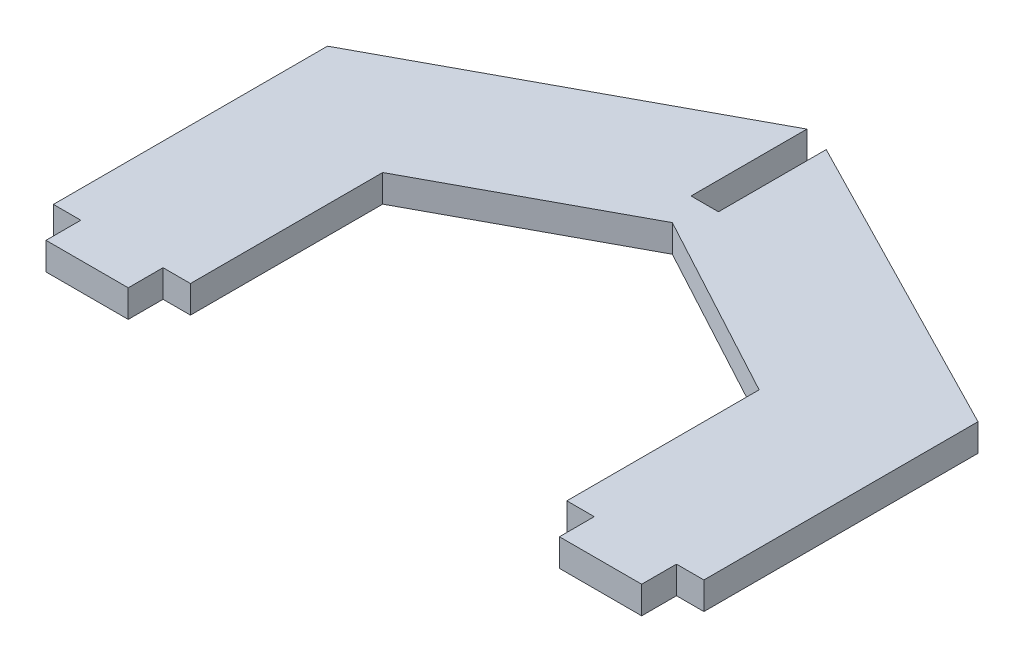
SolidWorks part; units mm, degrees
ref_plane "Front Plane" through (0, 0, 0) normal (0, 0, 1) x (1, 0, 0)
ref_plane "Top Plane" through (0, 0, 0) normal (0, 1, 0) x (1, 0, 0)
ref_plane "Right Plane" through (0, 0, 0) normal (1, 0, 0) x (0, 0, -1)
sketch "Sketch1" plane through (0, 0, 0) normal (0, 1, 0) x (1, 0, 0)
  line L0 (-72.7638, -36.4826) -> (-67.7638, -36.4826)
  line L1 (-67.7638, -36.4826) -> (-67.7638, -42.8326)
  line L2 (-67.7638, -42.8326) -> (-52.7638, -42.8326)
  line L3 (-52.7638, -42.8326) -> (-52.7638, -36.4826)
  line L4 (-52.7638, -36.4826) -> (-47.7638, -36.4826)
  line L5 (-47.7638, -36.4826) -> (-47.7638, -1.4097)
  line L6 (-47.7638, -1.4097) -> (-13.4344, 17.089)
  line L7 (-13.4344, 17.089) -> (20.8951, -1.4097)
  line L8 (20.8951, -1.4097) -> (20.8951, -36.4826)
  line L9 (20.8951, -36.4826) -> (25.8951, -36.4826)
  line L10 (25.8951, -36.4826) -> (25.8951, -42.8326)
  line L11 (25.8951, -42.8326) -> (40.8951, -42.8326)
  line L12 (40.8951, -42.8326) -> (40.8951, -36.4826)
  line L13 (40.8951, -36.4826) -> (45.8951, -36.4826)
  line L14 (45.8951, -36.4826) -> (45.8951, 13.5174)
  line L15 (45.8951, 13.5174) -> (-10.9344, 42.6616)
  line L16 (-15.9344, 44.1404) -> (-72.7638, 13.5174)
  line L17 (-72.7638, 13.5174) -> (-72.7638, -36.4826)
  line L18 (-13.4344, -987.0002) -> (-13.4344, 49012.9998) construction
  line L19 (-15.9344, 44.1404) -> (-15.9344, 23.0033)
  line L20 (-15.9344, 23.0033) -> (-10.9344, 23.0033)
  line L21 (-10.9344, 23.0033) -> (-10.9344, 42.6616)
  point P11 (-13.4344, 23.0033)
  dimension "D1" = 5
  dimension "D2" = 5
  dimension "D3" = 15
  dimension "D4" = 6.35
  dimension "D5" = 25
  dimension "D6" = 50
  dimension "D7" = 5
extrude "Boss-Extrude1" add sketch "Sketch1" along normal blind 5
